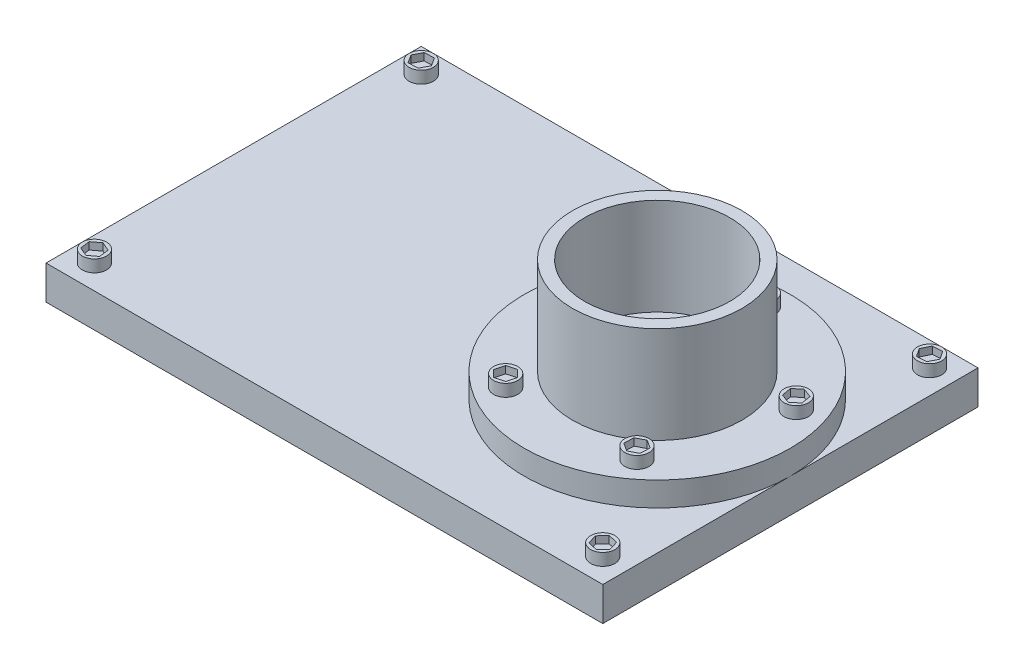
SolidWorks part; units mm, degrees
material "1060 Alloy"
ref_plane "Front Plane" through (0, 0, 0) normal (0, 0, 1) x (1, 0, 0)
ref_plane "Top Plane" through (0, 0, 0) normal (0, 1, 0) x (1, 0, 0)
ref_plane "Right Plane" through (0, 0, 0) normal (1, 0, 0) x (0, 0, -1)
sketch "Sketch1" plane through (0, 0, 0) normal (0, 1, 0) x (1, 0, 0)
  line L1 (0, 0) -> (230, 0)
  line L2 (0, 0) -> (0, 155)
  line L3 (0, 155) -> (230, 155)
  line L4 (230, 0) -> (230, 155)
  dimension "D1" = 230
  dimension "D2" = 155
extrude "Boss-Extrude1" add sketch "Sketch1" along normal blind 14
sketch "Sketch2" plane through (0, 14, 0) normal (0, 1, 0) x (1, 0, 0)
  line L1 (230, 0) -> (230, 155) construction
  line L2 (0, 77.5) -> (355.5558, 77.5) construction
  line L3 (0, 155) -> (0, 0) construction
  circle A0 centre (175, 77.5) radius 55
  dimension "D1" = 110
  dimension "D3" = 55
extrude "Boss-Extrude2" add sketch "Sketch2" along normal blind 10
sketch "Sketch4" plane through (0, 24, 0) normal (0, 1, 0) x (1, 0, 0)
  circle A1 centre (175, 77.5) radius 35
  dimension "D1" = 70
extrude "Boss-Extrude3" add sketch "Sketch4" along normal blind 40
sketch "Sketch8" plane through (0, 64, 0) normal (0, 1, 0) x (1, 0, 0)
  circle A1 centre (175, 77.5) radius 30
  dimension "D1" = 60
extrude "Cut-Extrude1" cut sketch "Sketch8" against normal blind 40
sketch "Sketch9" plane through (0, 24, 0) normal (0, 1, 0) x (1, 0, 0)
  circle A1 centre (175, 77.5) radius 30
  dimension "D1" = 60
sketch "Sketch11" plane through (0, 14, 0) normal (0, 1, 0) x (1, 0, 0)
  line L0 (0, 0) -> (230, 0) construction
  line L1 (0, 155) -> (0, 0) construction
  line L2 (230, 155) -> (0, 155) construction
  line L3 (230, 77.5) -> (230, 155) construction
  line L4 (230, 0) -> (230, 77.5) construction
  circle A0 centre (10, 10) radius 5
  circle A1 centre (10, 145) radius 5
  circle A2 centre (220, 145) radius 5
  circle A3 centre (220, 10) radius 5
  dimension "D1" = 10
  dimension "D2" = 10
  dimension "D6" = 10
  dimension "D7" = 10
  dimension "D8" = 10
  dimension "D9" = 10
  dimension "D10" = 10
  dimension "D11" = 10
  dimension "D12" = 10
  dimension "D3" = 10
  dimension "D4" = 10
  dimension "D5" = 10
extrude "Boss-Extrude5" add sketch "Sketch11" along normal blind 5
sketch "Sketch13" plane through (0, 19, 0) normal (0, 1, 0) x (1, 0, 0)
  line L1 (13.2245, 12.4364) -> (9.5022, 14.0107)
  line L2 (9.5022, 14.0107) -> (6.2778, 11.5742)
  line L3 (6.2778, 11.5742) -> (6.7755, 7.5636)
  line L4 (6.7755, 7.5636) -> (10.4978, 5.9893)
  line L5 (10.4978, 5.9893) -> (13.7222, 8.4258)
  line L6 (13.7222, 8.4258) -> (13.2245, 12.4364)
  line L7 (11.873, 148.5812) -> (7.8351, 148.4127)
  line L8 (7.8351, 148.4127) -> (5.9621, 144.8315)
  line L9 (5.9621, 144.8315) -> (8.127, 141.4188)
  line L10 (8.127, 141.4188) -> (12.1649, 141.5873)
  line L11 (12.1649, 141.5873) -> (14.0379, 145.1685)
  line L12 (14.0379, 145.1685) -> (11.873, 148.5812)
  line L13 (224.0334, 145.2542) -> (221.7965, 148.6202)
  line L14 (221.7965, 148.6202) -> (217.7631, 148.3659)
  line L15 (217.7631, 148.3659) -> (215.9666, 144.7458)
  line L16 (215.9666, 144.7458) -> (218.2035, 141.3798)
  line L17 (218.2035, 141.3798) -> (222.2369, 141.6341)
  line L18 (222.2369, 141.6341) -> (224.0334, 145.2542)
  line L19 (222.7332, 12.977) -> (218.7884, 13.8556)
  line L20 (218.7884, 13.8556) -> (216.0552, 10.8785)
  line L21 (216.0552, 10.8785) -> (217.2668, 7.023)
  line L22 (217.2668, 7.023) -> (221.2116, 6.1444)
  line L23 (221.2116, 6.1444) -> (223.9448, 9.1215)
  line L24 (223.9448, 9.1215) -> (222.7332, 12.977)
  circle A0 centre (10, 10) radius 3.5 construction
  circle A1 centre (10, 145) radius 3.5 construction
  circle A2 centre (220, 145) radius 3.5 construction
  circle A3 centre (220, 10) radius 3.5 construction
extrude "Cut-Extrude3" cut sketch "Sketch13" against normal blind 3
sketch "Sketch14" plane through (0, 24, 0) normal (0, 1, 0) x (1, 0, 0)
  circle A0 centre (173.8708, 122.5) radius 5
  circle A1 centre (175, 77.5) radius 55 construction
  circle A2 centre (217.4486, 92.4797) radius 5
  circle A3 centre (202.3638, 41.7579) radius 5
  circle A4 centre (149.4632, 40.4305) radius 5
  circle A5 centre (131.8535, 90.3319) radius 5
  point P15 (175, 77.5)
  dimension "D1" = 10
  dimension "D2" = 45
  dimension "D3" = 5
extrude "Boss-Extrude8" add sketch "Sketch14" along normal blind 5
sketch "Sketch15" plane through (0, 29, 0) normal (0, 1, 0) x (1, 0, 0)
  line L0 (221.229, 91.0508) -> (220.5763, 95.0391)
  line L1 (176.398, 125.6538) -> (172.4031, 126.2655)
  line L2 (172.4031, 126.2655) -> (169.8759, 123.1117)
  line L3 (169.8759, 123.1117) -> (171.3437, 119.3462)
  line L4 (171.3437, 119.3462) -> (175.3385, 118.7345)
  line L5 (175.3385, 118.7345) -> (177.8657, 121.8883)
  line L6 (177.8657, 121.8883) -> (176.398, 125.6538)
  line L7 (220.5763, 95.0391) -> (216.7959, 96.4681)
  line L8 (216.7959, 96.4681) -> (213.6682, 93.9086)
  line L9 (213.6682, 93.9086) -> (214.3209, 89.9202)
  line L10 (214.3209, 89.9202) -> (218.1014, 88.4913)
  line L11 (218.1014, 88.4913) -> (221.229, 91.0508)
  line L12 (202.1731, 37.721) -> (205.7646, 39.5743)
  line L13 (205.7646, 39.5743) -> (205.9553, 43.6112)
  line L14 (205.9553, 43.6112) -> (202.5546, 45.7949)
  line L15 (202.5546, 45.7949) -> (198.9631, 43.9416)
  line L16 (198.9631, 43.9416) -> (198.7724, 39.9047)
  line L17 (198.7724, 39.9047) -> (202.1731, 37.721)
  line L18 (145.5649, 39.3645) -> (148.4373, 36.5215)
  line L19 (148.4373, 36.5215) -> (152.3356, 37.5875)
  line L20 (152.3356, 37.5875) -> (153.3615, 41.4966)
  line L21 (153.3615, 41.4966) -> (150.4891, 44.3396)
  line L22 (150.4891, 44.3396) -> (146.5908, 43.2735)
  line L23 (146.5908, 43.2735) -> (145.5649, 39.3645)
  line L24 (129.635, 93.71) -> (127.8188, 90.0996)
  line L25 (127.8188, 90.0996) -> (130.0373, 86.7215)
  line L26 (130.0373, 86.7215) -> (134.0721, 86.9538)
  line L27 (134.0721, 86.9538) -> (135.8883, 90.5641)
  line L28 (135.8883, 90.5641) -> (133.6698, 93.9422)
  line L29 (133.6698, 93.9422) -> (129.635, 93.71)
  circle A0 centre (173.8708, 122.5) radius 3.5 construction
  point P36 (175, 77.5)
  dimension "D1" = 5
extrude "Cut-Extrude4" cut sketch "Sketch15" against normal blind 3
